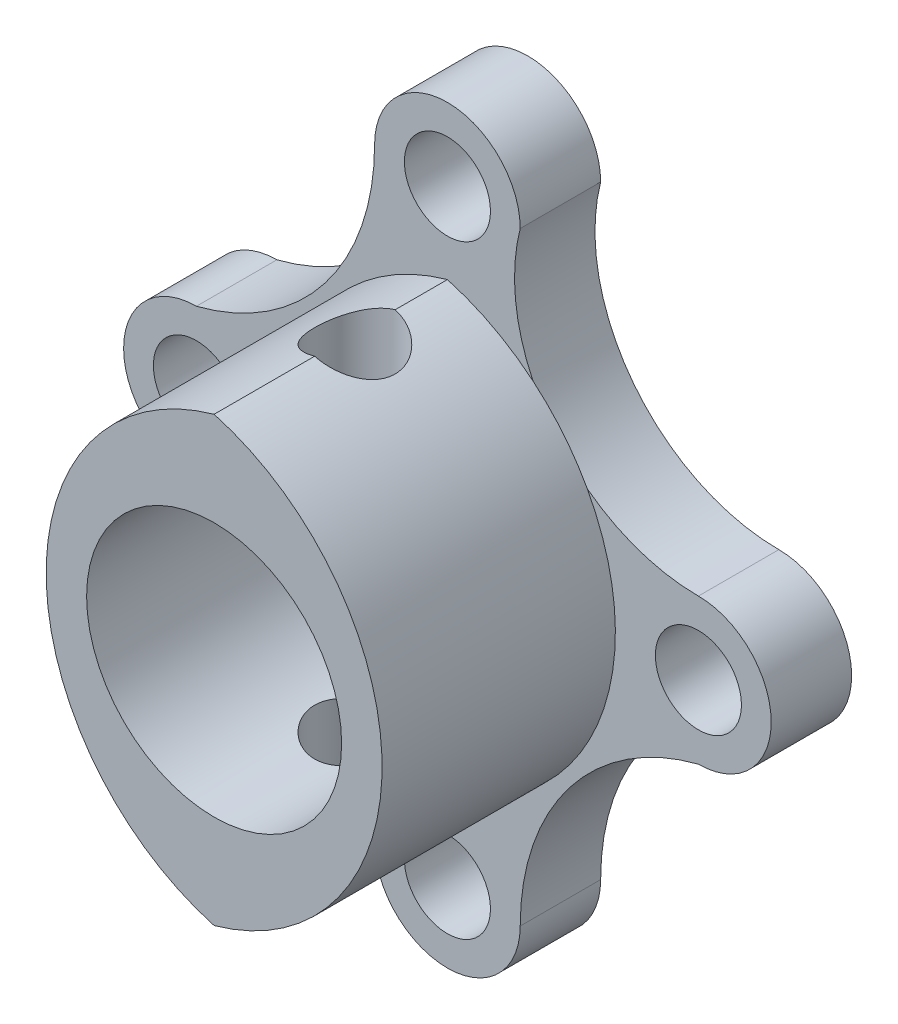
SolidWorks part; units mm, degrees
ref_plane "Front Plane" through (0, 0, 0) normal (0, 0, 1) x (1, 0, 0)
ref_plane "Top Plane" through (0, 0, 0) normal (0, 1, 0) x (1, 0, 0)
ref_plane "Right Plane" through (0, 0, 0) normal (1, 0, 0) x (0, 0, -1)
sketch "Sketch1" plane through (0, 0, 0) normal (0, 0, 1) x (1, 0, 0)
  line L0 (0, -8.1788) -> (0, 0) construction
  line L1 (0, 0) -> (0, 8.1788) construction
  line L2 (-6.5659, 0) -> (0, 0) construction
  line L3 (0, 0) -> (6.5659, 0) construction
  circle A0 centre (7.9248, 0) radius 1.3589
  circle A1 centre (0, 9.5377) radius 1.3589
  circle A2 centre (0, -9.5377) radius 1.3589
  circle A3 centre (-7.9248, 0) radius 1.3589
  arc A4 (2.1531, 8.7326) -> (-2.2987, 9.5377) centre (0, 9.5377) ccw
  arc A5 (-7.9248, 2.2987) -> (-7.9248, -2.2987) centre (-7.9248, 0) ccw
  arc A6 (-2.1531, -8.7326) -> (2.2987, -9.5377) centre (0, -9.5377) ccw
  arc A7 (7.9248, -2.2987) -> (7.9248, 2.2987) centre (7.9248, 0) ccw
  arc A8 (2.2987, -9.5377) -> (7.9248, -2.2987) centre (9.7689, -9.5377) cw
  arc A9 (7.9248, 2.2987) -> (2.2987, 9.5377) centre (7.9248, 8.1045) cw
  arc A10 (-2.2987, 9.5377) -> (-7.9248, 2.2987) centre (-9.7689, 9.5377) cw
  arc A11 (-7.9248, -2.2987) -> (-2.2987, -9.5377) centre (-7.9248, -8.1045) cw
  circle A13 centre (-7.9248, 0) radius 2.2987 construction
  circle A14 centre (0, -9.5377) radius 2.2987 construction
  circle A15 centre (7.9248, 0) radius 2.2987 construction
  circle A16 centre (0, 9.5377) radius 2.2987 construction
  point P11 (7.9248, 0)
  point P13 (2.2987, -7.9248)
  point P15 (0, 9.5377)
  point P16 (-7.1882, 0)
  point P17 (-7.9248, 0)
  point P19 (0, -9.5377)
  point P20 (2.2987, 7.9248)
  point P23 (2.2987, -9.5377)
  point P25 (10.2235, 0)
  point P27 (2.2987, 9.5377)
  point P33 (11.7856, 0)
  point P41 (-5.6261, 0)
  dimension "D1" = 13.1318
  dimension "D3" = 2.7178
  dimension "D4" = 0.9398
  dimension "D2" = 16.3576
extrude "Extrude1" add sketch "Sketch1" along normal blind 2.54
sketch "Sketch2" plane through (0, 0, 2.54) normal (0, 0, 1) x (1, 0, 0)
  arc A0 (0, 6.9903) -> (0, -6.9903) centre (1.9551, 0) ccw
  arc A1 (0, 6.9903) -> (0, -6.9903) centre (-1.9551, 0) cw
extrude "Extrude2" add sketch "Sketch2" along normal blind 7.366
sketch "Sketch3" plane through (0, 0, 9.906) normal (0, 0, 1) x (1, 0, 0)
  circle A0 centre (0, 0) radius 4.0259
extrude "Cut-Extrude1" cut sketch "Sketch3" against normal through all
sketch "Sketch4" plane through (0, 0, 0) normal (0, 1, 0) x (1, 0, 0)
  line L0 (-4.0259, -9.906) -> (4.0259, -9.906) construction
  circle A0 centre (0, -5.461) radius 1.27
  point P0 (0, -5.461)
  dimension "D1" = 4.445
extrude "Cut-Extrude2" cut sketch "Sketch4" against normal blind 7.366 and the other way through all
